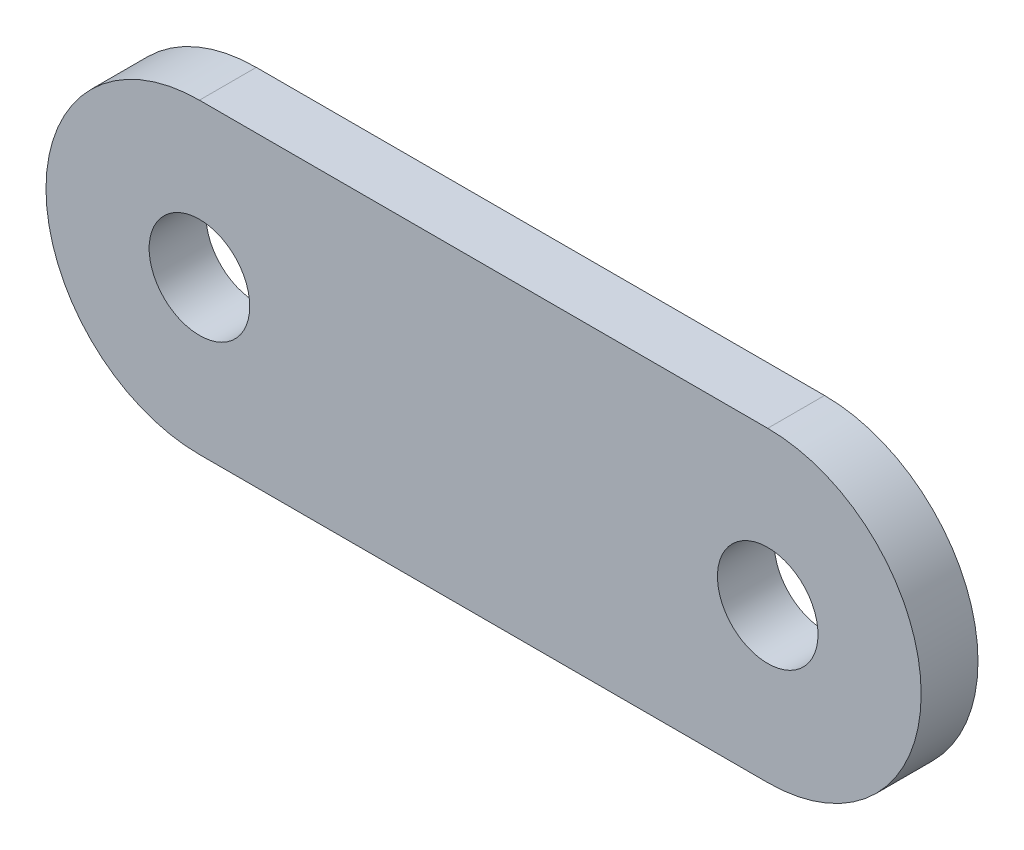
SolidWorks part; units mm, degrees
ref_plane "Front Plane" through (0, 0, 0) normal (0, 0, 1) x (1, 0, 0)
ref_plane "Top Plane" through (0, 0, 0) normal (0, 1, 0) x (1, 0, 0)
ref_plane "Right Plane" through (0, 0, 0) normal (1, 0, 0) x (0, 0, -1)
sketch "Sketch1" plane through (0, 0, 0) normal (0, 0, 1) x (1, 0, 0)
  line L0 (0, 0) -> (50, 0) construction
  line L1 (0, 13.5) -> (50, 13.5)
  line L2 (0, -13.5) -> (50, -13.5)
  circle A0 centre (0, 0) radius 4.425
  circle A1 centre (0, 0) radius 13.5
  circle A2 centre (50, 0) radius 4.425
  circle A3 centre (50, 0) radius 13.5
  dimension "D1" = 8.85
  dimension "D2" = 27
  dimension "D3" = 50
extrude "Boss-Extrude1" add sketch "Sketch1" along normal blind 5
